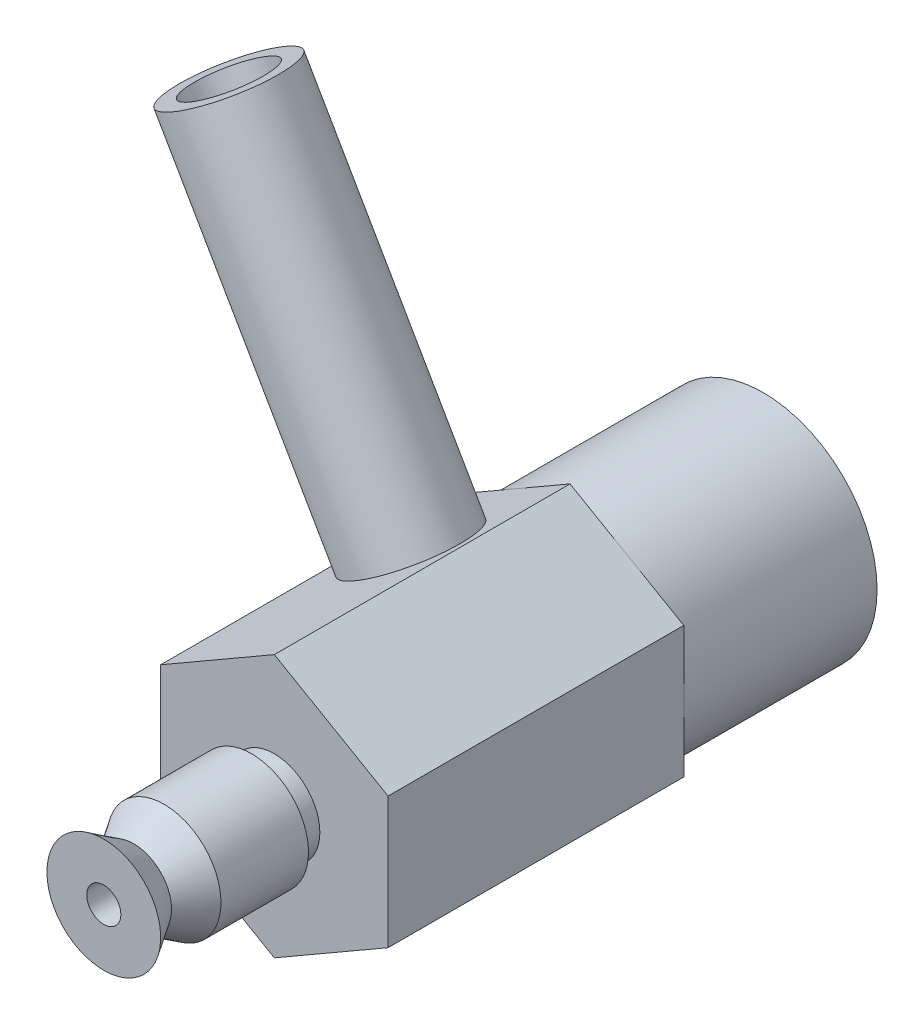
SolidWorks part; units mm, degrees
material "SKD11淬火HRC56-60"
ref_plane "前基準面" through (0, 0, 0) normal (0, 0, 1) x (1, 0, 0)
ref_plane "上基準面" through (0, 0, 0) normal (0, 1, 0) x (1, 0, 0)
ref_plane "右基準面" through (0, 0, 0) normal (1, 0, 0) x (0, 0, -1)
sketch "草图1" plane through (0, 0, 0) normal (0, 0, 1) x (1, 0, 0)
  circle A0 centre (0, 0) radius 5
  dimension "D1" = 10
extrude "凸台-拉伸1" add sketch "草图1" along normal blind 8.5
sketch "草图2" plane through (0, 0, 8.5) normal (0, 0, 1) x (1, 0, 0)
  line L0 (0, 0) -> (0, 4.3308) construction
  line L1 (5, 2.8868) -> (0, 5.7735)
  line L2 (0, 5.7735) -> (-5, 2.8868)
  line L3 (-5, 2.8868) -> (-5, -2.8868)
  line L4 (-5, -2.8868) -> (0, -5.7735)
  line L5 (0, -5.7735) -> (5, -2.8868)
  line L6 (5, -2.8868) -> (5, 2.8868)
  circle A0 centre (0, 0) radius 5 construction
  dimension "D1" = 10
extrude "凸台-拉伸2" add sketch "草图2" along normal blind 13
sketch "草图3" plane through (0, 0, 21.5) normal (0, 0, 1) x (1, 0, 0)
  circle A0 centre (0, 0) radius 2
  dimension "D1" = 4
extrude "凸台-拉伸3" add sketch "草图3" along normal blind 1
sketch "草图4" plane through (0, 0, 0) normal (0, 1, 0) x (1, 0, 0)
  line L0 (0, -22.5) -> (0, -28.7825) construction
  line L1 (-2, -22.5) -> (2, -22.5) construction
  line L2 (0, -22.5) -> (2.5, -22.5)
  line L3 (2.5, -22.5) -> (2.5, -26.3475)
  line L4 (2.5, -26.3475) -> (1.6642, -27.6834)
  line L5 (1.6642, -27.6834) -> (2.5, -29)
  line L6 (2.5, -29) -> (0, -29)
  line L7 (0, -22.5) -> (0, -29)
  line L8 (5, 0) -> (-5, 0) construction
  dimension "D1" = 2.5
  dimension "D2" = 29
revolve "旋转1" add sketch "草图4" angle 360 about L0
sketch "草图5" plane through (0, 0, 29) normal (0, 0, 1) x (1, 0, 0)
  circle A0 centre (0, 0) radius 0.75
  dimension "D1" = 1.5
extrude "切除-拉伸1" cut sketch "草图5" against normal blind 15
sketch "草图6" plane through (-2.5, 4.3301, 0) normal (-0.5, 0.866, 0) x (0.866, 0.5, 0)
  line L0 (0, -8.5) -> (0, -21.5) construction
  line L1 (2.8868, -21.5) -> (-2.8868, -21.5) construction
  line L2 (5, 0) -> (-5, 0) construction
  circle A0 centre (0, -13) radius 2.5
  dimension "D1" = 5
  dimension "D2" = 13
extrude "凸台-拉伸4" add sketch "草图6" along normal blind 16
sketch "草图7" plane through (-10.5, 18.1865, 0) normal (-0.5, 0.866, 0) x (0.866, 0.5, 0)
  circle A0 centre (0, -13) radius 1.75
  dimension "D1" = 3.5
extrude "切除-拉伸2" cut sketch "草图7" against normal blind 22
hole_wizard "M4 螺纹孔1" positions "草图9" profile "草图8" tap size "M4" standard "ISO"
sketch "草图9" plane through (0, 0, 0) normal (0, 0, -1) x (-1, 0, 0)
  point P0 (0, 0)
sketch "草图8" plane through (0, 0, 0) normal (1, 0, 0) x (0, 1, 0)
  line L0 (0, 0) -> (0, 11.0914)
  line L1 (0, 11.0914) -> (1.65, 10.1)
  line L2 (1.65, 10.1) -> (1.65, 0)
  line L5 (1.65, 0) -> (0, 0)
  line L10 (0, 11.0914) -> (-1.65, 10.1) construction
  line L11 (0, -6.35) -> (0, 107.95) construction
  dimension "螺纹孔钻头直径" = 3.3
  dimension "螺纹孔钻头深度" = 10.1
  dimension "导头角度" = 118
cosmetic thread "孔螺蚊线1" parameters "D1"=8, "D2"=4
